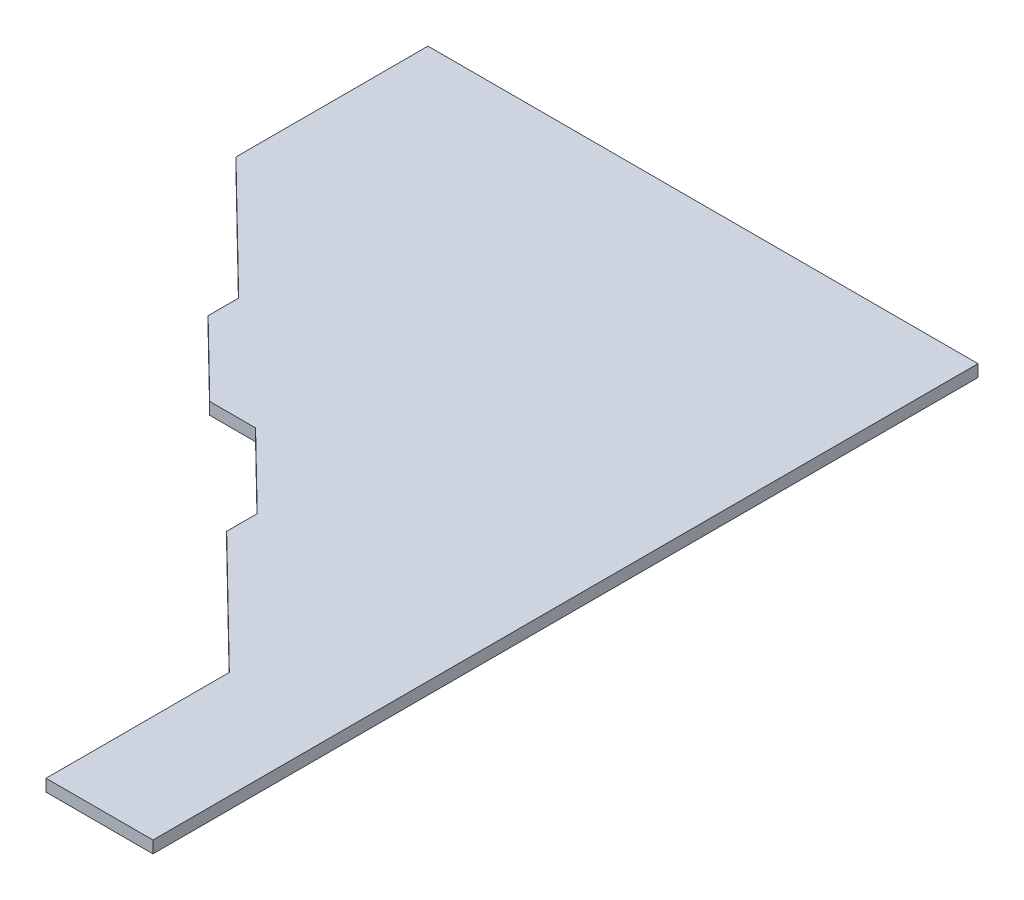
SolidWorks part; units mm, degrees
ref_plane "Front Plane" through (0, 0, 0) normal (0, 0, 1) x (1, 0, 0)
ref_plane "Top Plane" through (0, 0, 0) normal (0, 1, 0) x (1, 0, 0)
ref_plane "Right Plane" through (0, 0, 0) normal (1, 0, 0) x (0, 0, -1)
sketch "Sketch1" plane through (0, 0, 0) normal (0, 1, 0) x (1, 0, 0)
  line L0 (0, 0) -> (0, 68.58)
  line L1 (0, 68.58) -> (-45.72, 68.58)
  line L2 (-45.72, 68.58) -> (-45.72, 52.62)
  line L3 (-45.72, 52.62) -> (-35.4489, 42.5729)
  line L4 (-35.4489, 42.5729) -> (-35.4489, 40.0329)
  line L5 (-35.4489, 40.0329) -> (-29.21, 33.93)
  line L6 (-29.21, 33.93) -> (-25.4, 33.93)
  line L7 (-25.4, 33.93) -> (-19.1611, 27.8271)
  line L8 (-19.1611, 27.8271) -> (-19.1611, 25.2871)
  line L9 (-19.1611, 25.2871) -> (-8.89, 15.24)
  line L10 (-8.89, 15.24) -> (-8.89, 0)
  line L11 (-8.89, 0) -> (0, 0)
  dimension "D1" = 68.58
  dimension "D2" = 45.72
  dimension "D3" = 15.96
  dimension "D4" = 8.89
  dimension "D5" = 15.24
  dimension "D6" = 14.368
  dimension "D7" = 2.54
  dimension "D8" = 3.81
  dimension "D9" = 2.54
extrude "Boss-Extrude1" add sketch "Sketch1" along normal blind 1
